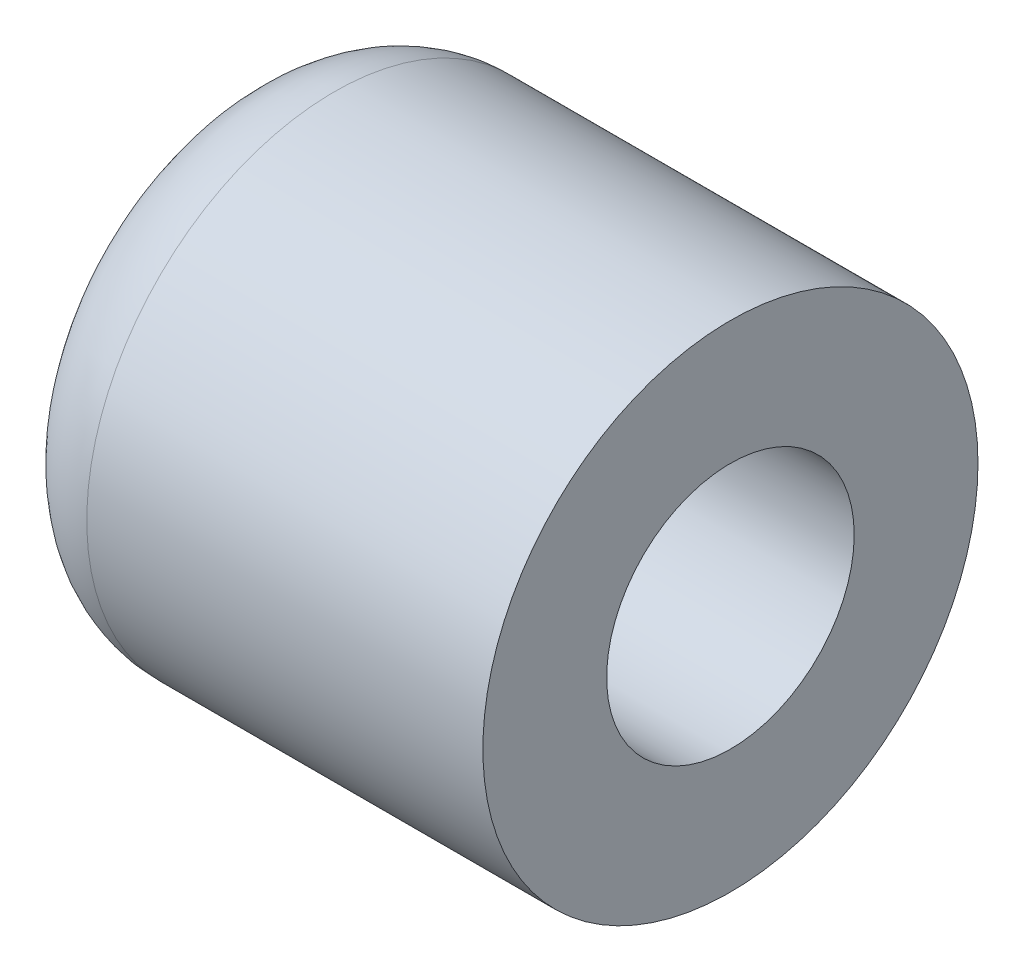
SolidWorks part; units mm, degrees
material "Gomma"
ref_plane "Piano frontale" through (0, 0, 0) normal (0, 0, 1) x (1, 0, 0)
ref_plane "Piano superiore" through (0, 0, 0) normal (0, 1, 0) x (1, 0, 0)
ref_plane "Piano destro" through (0, 0, 0) normal (1, 0, 0) x (0, 0, -1)
sketch "Schizzo3" plane through (0, 0, 0) normal (1, 0, 0) x (0, 0, -1)
  circle A0 centre (0, 0) radius 5
  dimension "D1" = 10
extrude "Estrusione-Estrusione1" add sketch "Schizzo3" along normal blind 10
fillet "Raccordo1" radius 2 1 edges at (0, 0, -5)
sketch "Schizzo4" plane through (10, 0, 0) normal (1, 0, 0) x (0, 0, -1)
  circle A0 centre (0, 0) radius 2.5
  dimension "D1" = 5
extrude "Taglio-Estrusione1" cut sketch "Schizzo4" against normal blind 7
